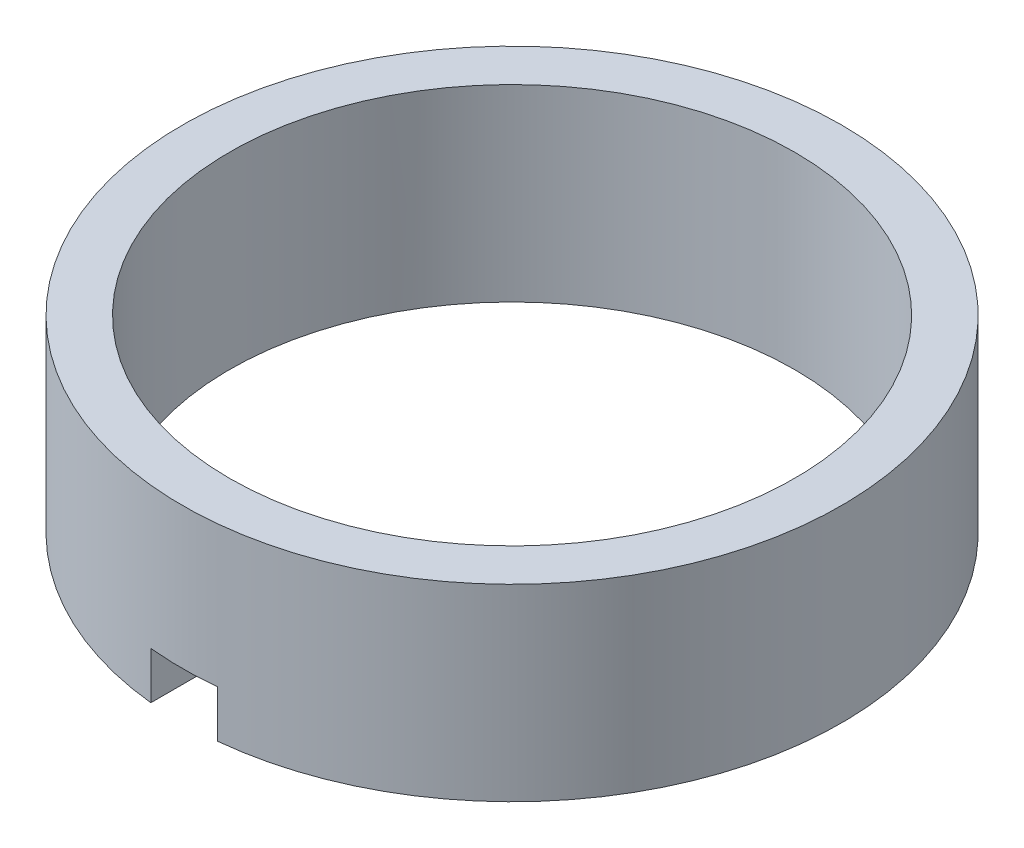
SolidWorks part; units mm, degrees
ref_plane "Front Plane" through (0, 0, 0) normal (1, 0, 0) x (0, 1, 0)
ref_plane "Top Plane" through (0, 0, 0) normal (0, 0, 1) x (0, 1, 0)
ref_plane "Right Plane" through (0, 0, 0) normal (0, 1, 0) x (-1, 0, 0)
sketch "Sketch1" plane through (0, 0, 0) normal (0, 0, 1) x (0, 1, 0)
  line L0 (-38.1, 133.35) -> (38.1, 133.35)
  line L1 (38.1, 133.35) -> (38.1, 114.3254)
  line L2 (38.1, 114.3254) -> (-38.1, 114.3254)
  line L3 (-38.1, 114.3254) -> (-38.1, 133.35)
  line L4 (-63.5, 0) -> (63.5, 0) construction
  point P6 (0, 0)
  dimension "D1" = 76.2
  dimension "D2" = 19.0246
  dimension "D3" = 133.35
  dimension "D4" = 38.1
revolve "Revolve1" add sketch "Sketch1" angle 360 about L4
sketch "Sketch2" plane through (0, 0, 0) normal (0, 1, 0) x (-1, 0, 0)
  line L1 (-13.4874, 0) -> (13.4874, 0)
  line L2 (-13.4874, 0) -> (-13.4874, 266.7)
  line L3 (-13.4874, 266.7) -> (13.4874, 266.7)
  line L4 (13.4874, 0) -> (13.4874, 266.7)
  point P2 (0, 0)
  dimension "D1" = 26.9748
  dimension "D2" = 266.7
extrude "Cut-Extrude2" cut sketch "Sketch2" along normal blind 19.05 from offset 38.1
